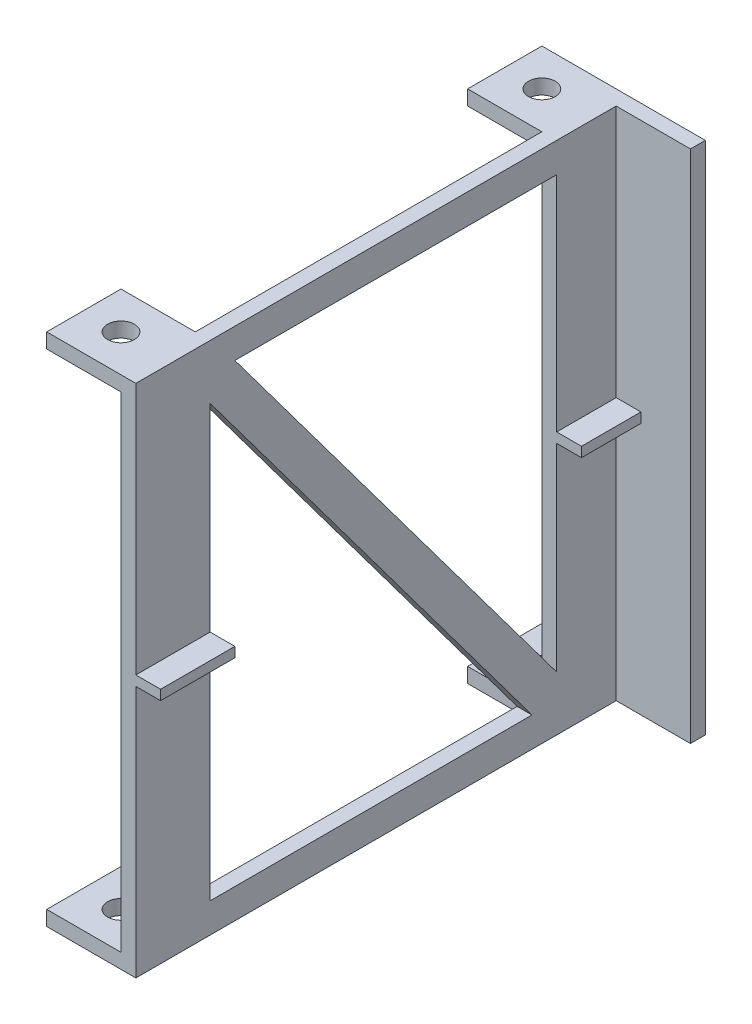
SolidWorks part; units mm, degrees
ref_plane "Front Plane" through (0, 0, 0) normal (0, 0, 1) x (1, 0, 0)
ref_plane "Top Plane" through (0, 0, 0) normal (0, 1, 0) x (1, 0, 0)
ref_plane "Right Plane" through (0, 0, 0) normal (1, 0, 0) x (0, 0, -1)
sketch "Sketch2" plane through (0, 0, 0) normal (0, 1, 0) x (1, 0, 0)
  line L1 (-11.9005, 8.2027) -> (3.0995, 8.2027)
  line L2 (-11.9005, 8.2027) -> (-11.9005, -6.7973)
  line L3 (-11.9005, -6.7973) -> (3.0995, -6.7973)
  line L4 (3.0995, 8.2027) -> (3.0995, -6.7973)
  dimension "D1" = 15
  dimension "D2" = 15
sketch "Sketch3" plane through (0, 0, 0) normal (0, 1, 0) x (1, 0, 0)
  line L1 (3.0995, 8.2027) -> (6.0995, 8.2027)
  line L2 (3.0995, 8.2027) -> (3.0995, -6.7973)
  line L3 (3.0995, -6.7973) -> (6.0995, -6.7973)
  line L4 (6.0995, 8.2027) -> (6.0995, -6.7973)
  dimension "D1" = 0
  dimension "D2" = 3
extrude "Boss-Extrude1" add sketch "Sketch2" along normal blind 3
extrude "Boss-Extrude2" add sketch "Sketch3" along normal blind 104
sketch "Sketch4" plane through (3.0995, 0, 0) normal (-1, 0, 0) x (0, 0, 1)
  line L0 (6.7973, 104) -> (6.7973, 3) construction
  line L1 (-8.2027, 104) -> (6.7973, 104)
  line L2 (-8.2027, 104) -> (-8.2027, 101)
  line L3 (-8.2027, 101) -> (6.7973, 101)
  line L4 (6.7973, 104) -> (6.7973, 101)
  dimension "D1" = 3
extrude "Boss-Extrude3" add sketch "Sketch4" along normal blind 15
sketch "Sketch5" plane through (0, 0, 0) normal (0, -1, 0) x (1, 0, 0)
  line L0 (3.0995, 6.7973) -> (3.0995, -8.2027) construction
  line L1 (-11.9005, -8.2027) -> (-11.9005, 6.7973) construction
  line L2 (-11.9005, 6.7973) -> (6.0995, 6.7973) construction
  circle A0 centre (-4.4005, -0.7027) radius 2.7
  dimension "D3" = 5.4
  dimension "D1" = 7.5
  dimension "D2" = 7.5
extrude "Cut-Extrude1" cut sketch "Sketch5" against normal through all
sketch "Sketch6" plane through (6.0995, 0, 0) normal (1, 0, 0) x (0, 0, -1)
  line L0 (-6.7973, 104) -> (-6.7973, 0) construction
  line L1 (-6.7973, 53) -> (8.2027, 53)
  line L2 (-6.7973, 53) -> (-6.7973, 51)
  line L3 (-6.7973, 51) -> (8.2027, 51)
  line L4 (8.2027, 53) -> (8.2027, 51)
  line L5 (8.2027, 104) -> (8.2027, 0) construction
  line L6 (-6.7973, 104) -> (8.2027, 104) construction
  line L7 (-6.7973, 0) -> (8.2027, 0) construction
  dimension "D1" = 51
  dimension "D2" = 51
extrude "Boss-Extrude4" add sketch "Sketch6" along normal blind 5
move or copy body "Body-Move/Copy2" bodies to move or copy 105 copy yes number of copies 1 translate (0, 0, 85) parameters "D1"=0, "D2"=0, "D3"=85
ref_plane "Plane1" through (6.0995, 0, 0) normal (-1, 0, 0) x (0, 0, 1)
sketch "Sketch8" plane through (6.0995, 0, 0) normal (-1, 0, 0) x (0, 0, 1)
  line L0 (76.7973, 104) -> (76.7973, 53) construction
  line L1 (6.7973, 104) -> (76.7973, 104)
  line L2 (6.7973, 104) -> (6.7973, 98)
  line L3 (6.7973, 98) -> (71.7973, 98)
  line L4 (76.7973, 104) -> (76.7973, 98)
  line L5 (76.7973, 51) -> (76.7973, 0) construction
  line L6 (6.7973, 0) -> (76.7973, 0)
  line L7 (6.7973, 0) -> (6.7973, 6)
  line L8 (11.7973, 6) -> (76.7973, 6)
  line L9 (76.7973, 0) -> (76.7973, 6)
  line L10 (6.7973, 11) -> (71.7973, 98)
  line L11 (6.7973, 51) -> (6.7973, 0) construction
  line L12 (76.7973, 93) -> (11.7973, 6)
  line L13 (76.7973, 93) -> (76.7973, 98)
  line L14 (6.7973, 11) -> (6.7973, 6)
  dimension "D1" = 6
  dimension "D2" = 6
  dimension "D3" = 5
  dimension "D4" = 5
  dimension "D5" = 5
  dimension "D6" = 5
extrude "Boss-Extrude5" add sketch "Sketch8" along normal blind 3
sketch "Sketch9" plane through (6.0995, 0, 0) normal (1, 0, 0) x (0, 0, -1)
  line L0 (-91.7973, 0) -> (8.2027, 0) construction
  line L1 (8.2027, 104) -> (5.2027, 104)
  line L2 (8.2027, 104) -> (8.2027, 0)
  line L3 (8.2027, 0) -> (5.2027, 0)
  line L4 (5.2027, 104) -> (5.2027, 0)
  dimension "D1" = 3
extrude "Boss-Extrude6" add sketch "Sketch9" along normal blind 15
